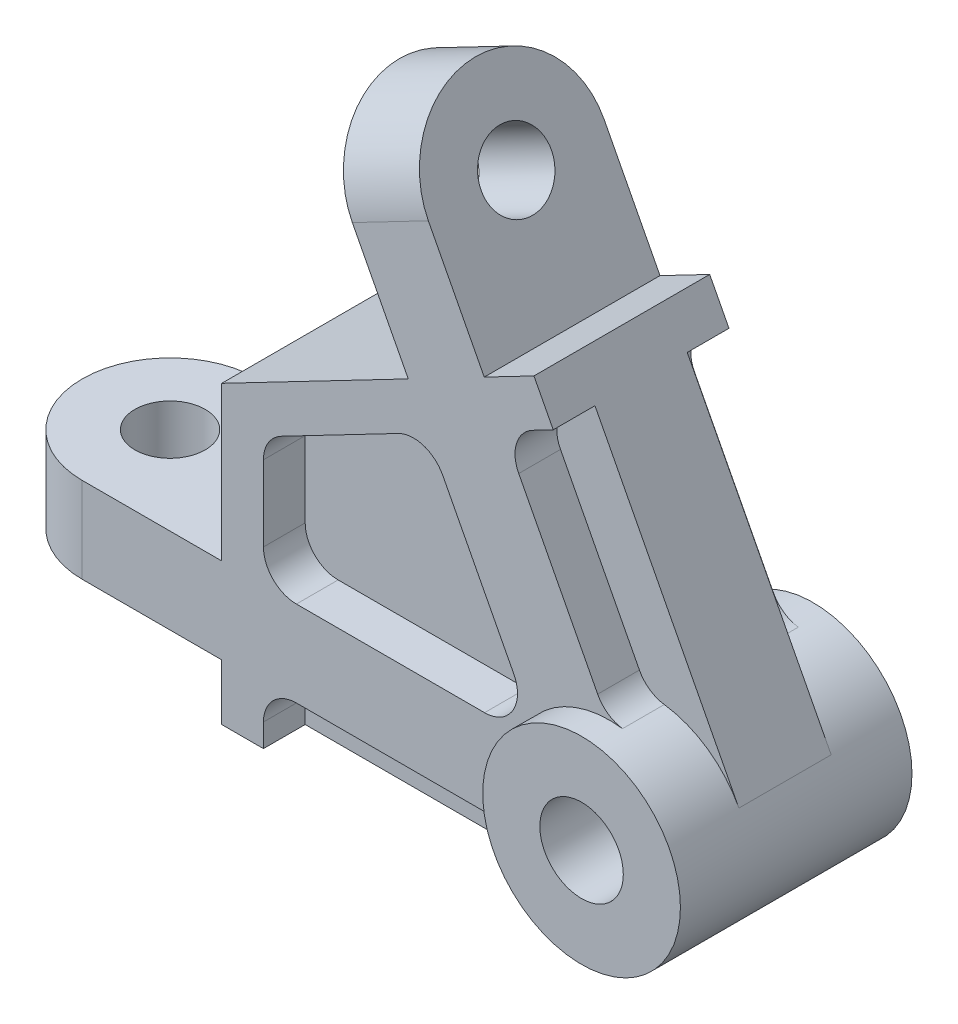
SolidWorks part; units mm, degrees
material "AISI 1020"
ref_plane "Front Plane" through (0, 0, 0) normal (0, 0, 1) x (1, 0, 0)
ref_plane "Top Plane" through (0, 0, 0) normal (0, 1, 0) x (1, 0, 0)
ref_plane "Right Plane" through (0, 0, 0) normal (1, 0, 0) x (0, 0, -1)
sketch "Sketch2" plane through (0, 0, 0) normal (0, 1, 0) x (1, 0, 0)
  line L0 (0, 0) -> (-120, 0) construction
  line L1 (0, -20) -> (-120, -20)
  line L2 (0, 20) -> (-120, 20)
  line L3 (0, 30.8495) -> (0, -33.8206) construction
  line L4 (0, 20) -> (0, -20)
  circle A0 centre (-120, 0) radius 8
  arc A1 (-120, 20) -> (-120, -20) centre (-120, 0) ccw
  point P2 (0, 0)
  dimension "D3" = 16
  dimension "D1" = 40
  dimension "D2" = 120
extrude "Boss-Extrude1" add sketch "Sketch2" along normal mid plane 19.5
ref_plane "Plane1" through (0, 0, 0) normal (0.887, 0.4617, 0) x (0.4617, -0.887, 0)
sketch "Sketch3" plane through (0, 0, 0) normal (0.887, 0.4617, 0) x (0.4617, -0.887, 0)
  line L0 (0, 0) -> (-108, 0) construction
  line L1 (0, -20) -> (-108, -20)
  line L2 (0, 20) -> (-108, 20)
  line L3 (0, 20) -> (0, -20)
  arc A0 (127.5, -20) -> (127.5, 20) centre (127.5, 0) ccw
  arc A1 (-108, 20) -> (-108, -20) centre (-108, 0) ccw
  circle A2 centre (-108, 0) radius 8
  point P2 (0, 0)
  dimension "D2" = 16
  dimension "D1" = 40
  dimension "Achange" = 108
extrude "Boss-Extrude2" add sketch "Sketch3" along normal mid plane 19.5
sketch "Sketch5" plane through (0, 0, 0) normal (0, 0, 1) x (1, 0, 0)
  line L0 (0, -22.5) -> (-88.25, -22.5)
  line L1 (19.9577, 10.3893) -> (-17.1867, 81.7432)
  line L2 (-88.25, -22.5) -> (-88.25, 44.75)
  line L3 (-120, 9.75) -> (-16.0675, 9.75) construction
  line L4 (-88.25, 44.75) -> (-17.1867, 81.7432)
  line L5 (10.1585, -19.5142) -> (-10.1585, 19.5142) construction
  circle A0 centre (0, 0) radius 22.5
  dimension "D1" = 45
  dimension "D2" = 31.75
  dimension "D3" = 35
extrude "Boss-Extrude3" add sketch "Sketch5" along normal mid plane 40 contours A0 L1 L4 L2 L0 | A0
sketch "Sketch6" plane through (0, 0, 0) normal (0, 0, 1) x (1, 0, 0)
  circle A0 centre (0, 0) radius 9.5
  dimension "D1" = 19
extrude "Cut-Extrude1" cut sketch "Sketch6" against normal mid plane 40
sketch "Sketch7" plane through (0, 0, 20) normal (0, 0, 1) x (1, 0, 0)
  line L0 (19.9577, 10.3893) -> (-17.1867, 81.7432) construction
  line L1 (-24.1095, 67.4293) -> (-12.8001, 73.3166)
  line L2 (-24.1095, 67.4293) -> (-0.7149, 22.4886)
  line L3 (-28.4961, 75.8559) -> (-41.2205, 100.2992) construction
  line L4 (-41.4062, 58.4252) -> (-16.0675, 9.75)
  line L5 (-78.75, 9.75) -> (-16.0675, 9.75)
  line L6 (-120, 9.75) -> (-88.25, 9.75) construction
  line L9 (-120, -9.75) -> (-88.25, -9.75) construction
  line L10 (-20.2778, -9.75) -> (-78.75, -9.75)
  line L12 (-78.75, -22.5) -> (-78.75, -9.75)
  line L13 (-78.75, -22.5) -> (-78.75, -9.75)
  line L14 (-12.8001, 73.3166) -> (19.9577, 10.3893)
  line L15 (-78.75, -22.5) -> (0, -22.5)
  line L23 (-78.75, 9.75) -> (-78.75, 38.9853)
  line L24 (-78.75, 38.9853) -> (-41.4062, 58.4252)
  line L25 (-78.75, 9.75) -> (-78.75, 38.9853)
  line L26 (-78.75, 38.9853) -> (-41.4062, 58.4252)
  arc A0 (-20.2778, -9.75) -> (-0.7149, 22.4886) centre (0, 0) ccw
  arc A1 (0, -22.5) -> (19.9577, 10.3893) centre (0, 0) ccw construction
  dimension "D1" = 9.5
  dimension "D4" = 9.5
extrude "Cut-Extrude3" cut sketch "Sketch7" against normal blind 9.5
fillet "Fillet1" radius 7.5 8 edges at (-0.7149, 22.4886, 15.25) (-24.1095, 67.4293, 15.25) (-20.2778, -9.75, 15.25) (-78.75, 38.9853, 15.25) (-78.75, -9.75, 15.25) (-78.75, 9.75, 15.25) (-16.0675, 9.75, 15.25) (-41.4062, 58.4252, 15.25)
mirror "Mirror1" about plane through (0, 0, 0) normal (0, 0, 1) of "Fillet1", "Cut-Extrude3"
sketch "Sketch9" plane through (0, 0, 20) normal (0, 0, 1) x (1, 0, 0)
  circle A0 centre (0, 0) radius 22.5
  arc A1 (-18.4085, -12.9375) -> (2.9756, 22.3024) centre (0, 0) ccw construction
  circle A2 centre (0, 0) radius 9.5
  circle A3 centre (0, 0) radius 9.5 construction
extrude "Boss-Extrude5" add sketch "Sketch9" along normal blind 6.35
mirror "Mirror2" about plane through (0, 0, 0) normal (0, 0, 1) of "Boss-Extrude5"
